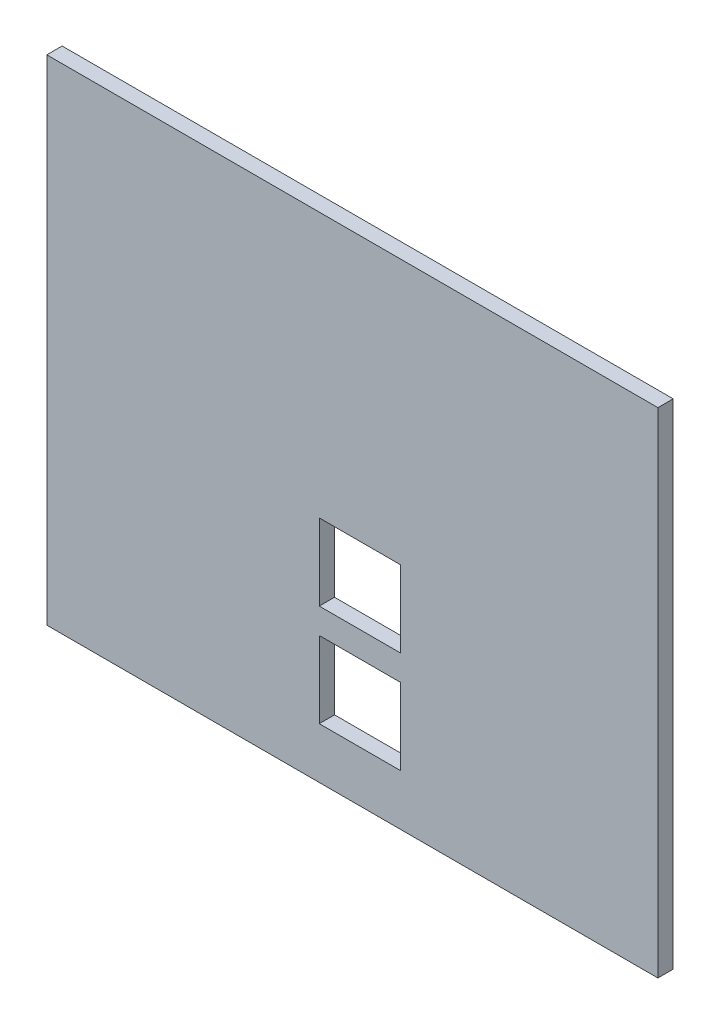
SolidWorks part; units mm, degrees
ref_plane "Plano frontal" through (0, 0, 0) normal (0, 0, 1) x (1, 0, 0)
ref_plane "Plano superior" through (0, 0, 0) normal (0, 1, 0) x (1, 0, 0)
ref_plane "Plano direito" through (0, 0, 0) normal (1, 0, 0) x (0, 0, -1)
sketch "Esboço1" plane through (0, 0, 0) normal (0, 0, 1) x (1, 0, 0)
  line L1 (60, -48.5) -> (-60, -48.5)
  line L2 (60, -48.5) -> (60, 48.5)
  line L3 (60, 48.5) -> (-60, 48.5)
  line L4 (-60, -48.5) -> (-60, 48.5)
  line L5 (60, -48.5) -> (-60, 48.5) construction
  line L6 (60, 48.5) -> (-60, -48.5) construction
  point P0 (0, 0)
  dimension "D1" = 120
  dimension "D2" = 97
extrude "Ressalto-extrusão1" add sketch "Esboço1" along normal blind 3
sketch "Esboço2" plane through (0, 0, 3) normal (0, 0, 1) x (1, 0, 0)
  line L0 (-60, -48.5) -> (60, -48.5) construction
  line L1 (-6.5, -23.5) -> (9.5, -23.5)
  line L2 (-6.5, -23.5) -> (-6.5, -38.5)
  line L3 (-6.5, -38.5) -> (9.5, -38.5)
  line L4 (9.5, -23.5) -> (9.5, -38.5)
  line L5 (60, -48.5) -> (60, 48.5) construction
  dimension "D1" = 15
  dimension "D2" = 16
  dimension "D3" = 10
  dimension "D4" = 50.5
extrude "Corte-extrusão1" cut sketch "Esboço2" against normal through all
pattern_linear "Padrão linear1" count 2 spacing 20 along (0, 1, 0) of "Corte-extrusão1"
